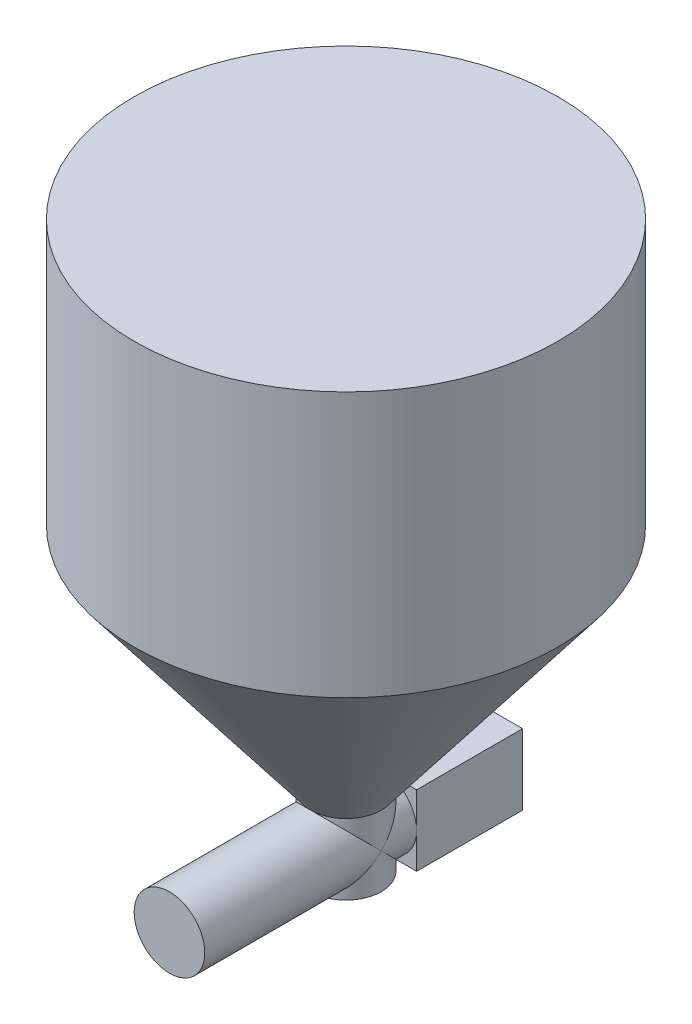
SolidWorks part; units mm, degrees
ref_plane "Alzado" through (0, 0, 0) normal (0, 0, 1) x (1, 0, 0)
ref_plane "Planta" through (0, 0, 0) normal (0, 1, 0) x (1, 0, 0)
ref_plane "Vista lateral" through (0, 0, 0) normal (1, 0, 0) x (0, 0, -1)
sketch "Croquis1" plane through (0, 0, 0) normal (0, 1, 0) x (1, 0, 0)
  circle A0 centre (0, 0) radius 300
  dimension "D1" = 600
ref_plane "Plano1" through (0, -700, 0) normal (0, 1, 0) x (1, 0, 0)
extrude "Saliente-Extruir1" add sketch "Croquis1" against normal blind 375 contours A0
sketch "Croquis2" plane through (0, -375, 0) normal (0, -1, 0) x (1, 0, 0)
  circle A0 centre (0, 0) radius 300
sketch "Croquis3" plane through (0, -700, 0) normal (0, 1, 0) x (1, 0, 0)
  circle A0 centre (0, 0) radius 50
  dimension "D1" = 100
loft "Recubrir1" add profiles "Croquis3", "Croquis2"
sketch "Croquis4" plane through (0, -700, 0) normal (0, -1, 0) x (1, 0, 0)
  circle A0 centre (0, 0) radius 50
extrude "Saliente-Extruir2" add sketch "Croquis4" along normal blind 100
ref_plane "Plano2" through (0, 0, -50) normal (0, 0, -1) x (-1, 0, 0)
sketch "Croquis5" plane through (0, 0, -50) normal (0, 0, -1) x (-1, 0, 0)
  line L0 (-50, -800) -> (50, -800) construction
  line L3 (0, -800) -> (0, -700) construction
  line L4 (330, -700) -> (-330, -700) construction
  circle A0 centre (0, -750) radius 50
extrude "Saliente-Extruir3" add sketch "Croquis5" against normal blind 300
sketch "Croquis6" plane through (0, 0, -50) normal (0, 0, -1) x (-1, 0, 0)
  line L0 (-50, -750) -> (50, -750) construction
  line L2 (-50, -700) -> (50, -700)
  line L3 (-50, -700) -> (-50, -800)
  line L4 (-50, -800) -> (50, -800)
  line L5 (50, -700) -> (50, -800)
  line L6 (-50, -700) -> (50, -800) construction
  line L7 (-50, -800) -> (50, -700) construction
  arc A0 (0, -700) -> (0, -800) centre (0, -750) ccw construction
  arc A1 (0, -800) -> (0, -700) centre (0, -750) ccw construction
  point P8 (0, -750)
  dimension "D1" = 100
  dimension "D2" = 100
extrude "Saliente-Extruir4" add sketch "Croquis6" along normal blind 150
